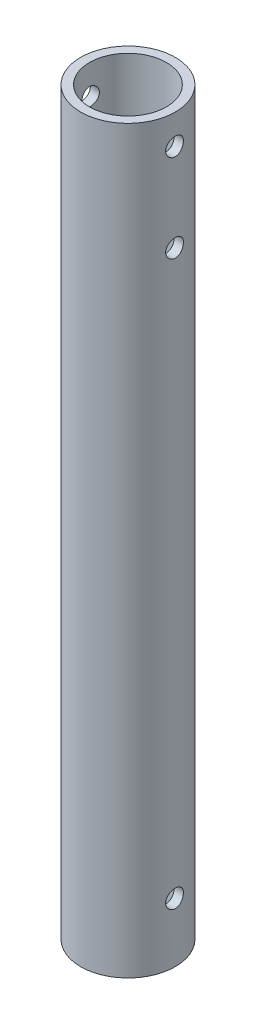
SolidWorks part; units mm, degrees
material "Hexcel AS4C (3000 丝)"
ref_plane "前视基准面" through (0, 0, 0) normal (0, 0, 1) x (1, 0, 0)
ref_plane "上视基准面" through (0, 0, 0) normal (0, 1, 0) x (1, 0, 0)
ref_plane "右视基准面" through (0, 0, 0) normal (1, 0, 0) x (0, 0, -1)
sketch "草图1" plane through (0, 0, 0) normal (0, 1, 0) x (1, 0, 0)
  circle A0 centre (0, 0) radius 8
  circle A1 centre (0, 0) radius 6.5
extrude "凸台-拉伸1" add sketch "草图1" along normal blind 125
sketch "草图3" plane through (0, 0, 0) normal (1, 0, 0) x (0, 0, -1)
  circle A0 centre (0, 119.9686) radius 1.5
  circle A1 centre (0, 105.1321) radius 1.5
  circle A2 centre (0, 10) radius 1.5
extrude "切除-拉伸2" cut sketch "草图3" against normal mid plane 125
